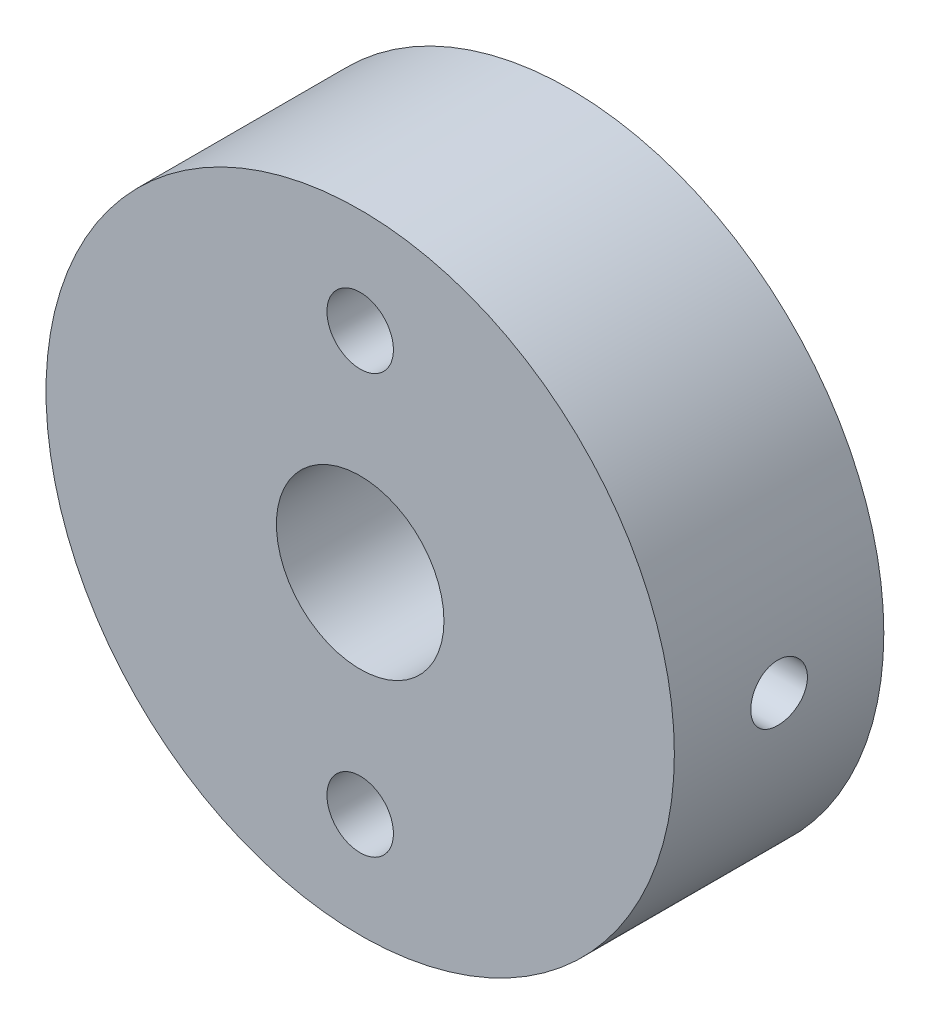
SolidWorks part; units mm, degrees
ref_plane "Front Plane" through (0, 0, 0) normal (0, 0, 1) x (1, 0, 0)
ref_plane "Top Plane" through (0, 0, 0) normal (0, 1, 0) x (1, 0, 0)
ref_plane "Right Plane" through (0, 0, 0) normal (1, 0, 0) x (0, 0, -1)
sketch "Sketch1" plane through (0, 0, 0) normal (0, 0, 1) x (1, 0, 0)
  circle A0 centre (0, 10) radius 1.5875
  circle A1 centre (0, 0) radius 15
  circle A6 centre (0, 0) radius 4
  circle A8 centre (0, -10) radius 1.5875
  circle A10 centre (-10, 0) radius 1.5875 [skipped]
  circle A11 centre (10, 0) radius 1.5875 [skipped]
  dimension "D1" = 4
extrude "Boss-Extrude2" add sketch "Sketch1" along normal blind 10
hole_wizard "#6-32 Tapped Hole1" positions "3DSketch1" profile "Sketch2" tap size "#6-32" standard "Ansi Inch"
sketch3d "3DSketch1"
  point P0 (0, 0, 0)
  point P3 (15, 0, 5)
sketch "Sketch2" plane through (15, 0, 5) normal (0, 1, 0) x (0, 0, -1)
  line L0 (0, 0) -> (0, 15.8117)
  line L1 (0, 15.8117) -> (1.3525, 14.999)
  line L2 (1.3525, 14.999) -> (1.3525, 0)
  line L5 (1.3525, 0) -> (0, 0)
  line L10 (0, 15.8117) -> (-1.3526, 14.999) construction
  line L11 (0, -6.35) -> (0, 107.95) construction
  dimension "Tap Drill Dia." = 2.7051
  dimension "Tap Drill Depth" = 14.999
  dimension "Drill Angle" = 118
cosmetic thread "Hole Thread1" parameters "D1"=7.112, "D2"=3.5052
